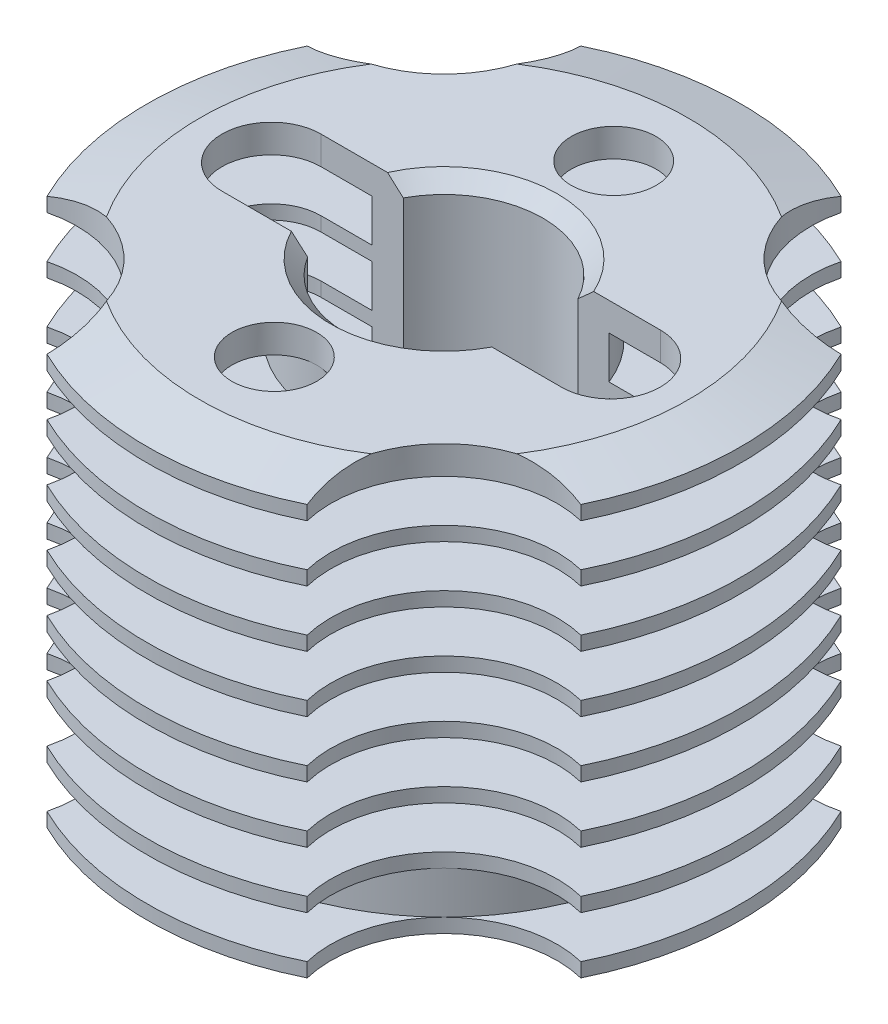
SolidWorks part; units mm, degrees
material "6061 Alloy"
ref_plane "Front" through (0, 0, 0) normal (0, 0, 1) x (1, 0, 0)
ref_plane "Top" through (0, 0, 0) normal (0, 1, 0) x (1, 0, 0)
ref_plane "Right" through (0, 0, 0) normal (1, 0, 0) x (0, 0, -1)
sketch "Sketch1" plane through (0, 0, 0) normal (0, 1, 0) x (1, 0, 0)
  circle A0 centre (0, 0) radius 21
extrude "Boss-Extrude1" add sketch "Sketch1" along normal blind 1
sketch "Sketch2" plane through (0, 1, 0) normal (0, 1, 0) x (1, 0, 0)
  circle A0 centre (0, 0) radius 16
extrude "Boss-Extrude2" add sketch "Sketch2" along normal blind 3
sketch "Sketch3" plane through (0, 4, 0) normal (0, 1, 0) x (1, 0, 0)
  circle A0 centre (0, 0) radius 21
extrude "Boss-Extrude3" add sketch "Sketch3" along normal blind 1
sketch "Sketch4" plane through (0, 5, 0) normal (0, 1, 0) x (1, 0, 0)
  circle A0 centre (0, 0) radius 9
extrude "Boss-Extrude4" add sketch "Sketch4" along normal blind 3
sketch "Sketch5" plane through (0, 8, 0) normal (0, 1, 0) x (1, 0, 0)
  circle A0 centre (0, 0) radius 21
extrude "Boss-Extrude5" add sketch "Sketch5" along normal blind 1
sketch "Sketch6" plane through (0, 9, 0) normal (0, 1, 0) x (1, 0, 0)
  circle A0 centre (0, 0) radius 9
extrude "Boss-Extrude6" add sketch "Sketch6" along normal blind 3
sketch "Sketch7" plane through (0, 12, 0) normal (0, 1, 0) x (1, 0, 0)
  circle A0 centre (0, 0) radius 21
extrude "Boss-Extrude7" add sketch "Sketch7" along normal blind 1
sketch "Sketch8" plane through (0, 13, 0) normal (0, 1, 0) x (1, 0, 0)
  circle A0 centre (0, 0) radius 9
extrude "Boss-Extrude8" add sketch "Sketch8" along normal blind 3
sketch "Sketch9" plane through (0, 16, 0) normal (0, 1, 0) x (1, 0, 0)
  circle A0 centre (0, 0) radius 21
extrude "Boss-Extrude9" add sketch "Sketch9" along normal blind 1
sketch "Sketch10" plane through (0, 17, 0) normal (0, 1, 0) x (1, 0, 0)
  circle A0 centre (0, 0) radius 9
extrude "Boss-Extrude10" add sketch "Sketch10" along normal blind 3
sketch "Sketch11" plane through (0, 20, 0) normal (0, 1, 0) x (1, 0, 0)
  circle A0 centre (0, 0) radius 21
extrude "Boss-Extrude11" add sketch "Sketch11" along normal blind 1
sketch "Sketch12" plane through (0, 21, 0) normal (0, 1, 0) x (1, 0, 0)
  circle A0 centre (0, 0) radius 9
extrude "Boss-Extrude12" add sketch "Sketch12" along normal blind 3
sketch "Sketch13" plane through (0, 24, 0) normal (0, 1, 0) x (1, 0, 0)
  circle A0 centre (0, 0) radius 21
extrude "Boss-Extrude13" add sketch "Sketch13" along normal blind 1
sketch "Sketch14" plane through (0, 25, 0) normal (0, 1, 0) x (1, 0, 0)
  circle A0 centre (0, 0) radius 9
extrude "Boss-Extrude14" add sketch "Sketch14" along normal blind 3
sketch "Sketch15" plane through (0, 28, 0) normal (0, 1, 0) x (1, 0, 0)
  circle A0 centre (0, 0) radius 21
extrude "Boss-Extrude15" add sketch "Sketch15" along normal blind 2
sketch "Sketch16" plane through (0, 30, 0) normal (0, 1, 0) x (1, 0, 0)
  circle A0 centre (0, 0) radius 7
extrude "Cut-Extrude1" cut sketch "Sketch16" against normal blind 26
sketch "Sketch17" plane through (0, 30, 0) normal (0, 1, 0) x (1, 0, 0)
  line L3 (12, -0.2024) -> (-12, -0.2024) construction
  line L4 (12, -0.2024) -> (-12, -0.2024) construction
  line L5 (12, -3.7024) -> (-12, -3.7024)
  line L6 (12, 3.2976) -> (-12, 3.2976)
  arc A0 (12, -3.7024) -> (12, 3.2976) centre (12, -0.2024) ccw
  arc A1 (-12, 3.2976) -> (-12, -3.7024) centre (-12, -0.2024) ccw
  point P10 (0, -0.2024)
extrude "Cut-Extrude2" cut sketch "Sketch17" against normal blind 25
sketch "Sketch18" plane through (0, 30, 0) normal (0, 1, 0) x (1, 0, 0)
  circle A0 centre (0, 12) radius 3
  circle A1 centre (0, -12) radius 3
extrude "Cut-Extrude3" cut sketch "Sketch18" against normal blind 24
sketch "Sketch19" plane through (0, 5, 0) normal (0, 1, 0) x (1, 0, 0)
  circle A0 centre (0, -12) radius 1.5
extrude "Cut-Extrude4" cut sketch "Sketch19" against normal through all
ref_plane "Plane1" through (0, 0, 0) normal (0, 0, 1) x (1, 0, 0)
sketch "Sketch21" plane through (0, 0, 0) normal (0, 0, 1) x (1, 0, 0)
  line L0 (0, 0) -> (0, 46.0161) construction
pattern_circular "CirPattern1" count 4 over 360 about axis through (0, 0, 0) along (0, 1, 0) of "Cut-Extrude4"
sketch "Sketch23" plane through (0, 0, 0) normal (0, -1, 0) x (1, 0, 0)
  circle A0 centre (0, 0) radius 7.5
extrude "Boss-Extrude16" add sketch "Sketch23" along normal blind 2
sketch "Sketch24" plane through (0, -2, 0) normal (0, -1, 0) x (1, 0, 0)
  circle A0 centre (0, 0) radius 2.5
  dimension "D1" = 5
extrude "Cut-Extrude7" cut sketch "Sketch24" against normal through all
cosmetic thread "Cosmetic Thread1" parameters "D1"=6, "D2"=6
chamfer "Chamfer4" distance 1 angle 45 1 edges at (0, -2, -2.5)
chamfer "Chamfer5" distance 1 angle 45 2 edges at (0, 30, -7) (0, 30, 7)
chamfer "Chamfer6" distance 1 angle 75 1 edges at (0, 30, 21)
ref_plane "Plane2" through (0, 30, 0) normal (0, 1, 0) x (1, 0, 0)
sketch "Sketch26" plane through (0, 30, 0) normal (0, 1, 0) x (1, 0, 0)
  line L0 (0, 0) -> (0, 27.7792) construction
  line L1 (0, 0) -> (-16.9706, 16.9706) construction
  circle A0 centre (-16.9706, 16.9706) radius 8
  dimension "D1" = 24
extrude "Cut-Extrude8" cut sketch "Sketch26" against normal through all
pattern_circular "CirPattern2" count 4 over 360 about axis through (0, 0, 0) along (0, 1, 0) of "Cut-Extrude8"
